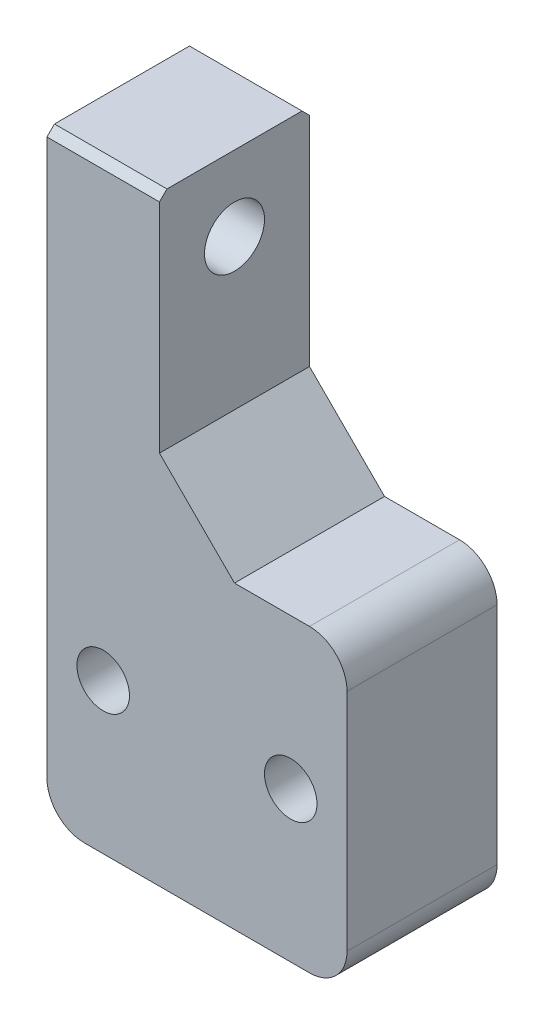
SolidWorks part; units mm, degrees
other "Objet de détail1"
ref_plane "Front" through (0, 0, 0) normal (0, 0, 1) x (1, 0, 0)
ref_plane "Top" through (0, 0, 0) normal (0, 1, 0) x (1, 0, 0)
ref_plane "Right" through (0, 0, 0) normal (1, 0, 0) x (0, 0, -1)
sketch "Esquisse1" plane through (0, 0, 0) normal (0, 0, 1) x (1, 0, 0)
  line L1 (0, 0) -> (40, 0)
  line L2 (0, 0) -> (0, 40)
  line L3 (0, 40) -> (40, 40)
  line L4 (40, 0) -> (40, 40)
  dimension "D1" = 40
  dimension "D2" = 40
extrude "Boss.-Extru.1" add sketch "Esquisse1" along normal blind 20
sketch "Esquisse2" plane through (0, 0, 20) normal (0, 0, 1) x (1, 0, 0)
  line L1 (0, 40) -> (15, 40)
  line L2 (0, 40) -> (0, 80)
  line L3 (0, 80) -> (15, 80)
  line L4 (15, 40) -> (15, 80)
  dimension "D1" = 15
  dimension "D2" = 40
extrude "Boss.-Extru.2" add sketch "Esquisse2" against normal up to vertex (20 mm away) up to point (40, 40, 0)
sketch "Esquisse3" plane through (0, 0, 20) normal (0, 0, 1) x (1, 0, 0)
  line L0 (40, 20) -> (0, 20) construction
  line L2 (40, 0) -> (40, 40) construction
  line L3 (0, 80) -> (0, 0) construction
  line L4 (20, 20) -> (20, 0) construction
  line L5 (0, 0) -> (40, 0) construction
  circle A0 centre (7.5, 20) radius 3.5
  circle A1 centre (32.5, 20) radius 3.5
  dimension "D1" = 25
  dimension "D2" = 7
extrude "Enlèv. mat.-Extru.1" cut sketch "Esquisse3" against normal through all both and the other way through all
sketch "Esquisse4" plane through (0, 0, 0) normal (-1, 0, 0) x (0, 0, 1)
  line L0 (10, 80) -> (10, 70) construction
  line L1 (0, 80) -> (20, 80) construction
  circle A0 centre (10, 70) radius 4
  dimension "D1" = 8
  dimension "D2" = 10
extrude "Enlèv. mat.-Extru.2" cut sketch "Esquisse4" against normal through all both and the other way through all
fillet "Congé1" radius 5 3 edges at (0, 0, 10) (40, 0, 10) (40, 40, 10)
chamfer "Chanfrein1" distance 10 angle 45 1 edges at (15, 40, 10)
chamfer "Chanfrein2" distance 1 angle 45 2 edges at (7.5, 80, 20) (7.5, 80, 0)
